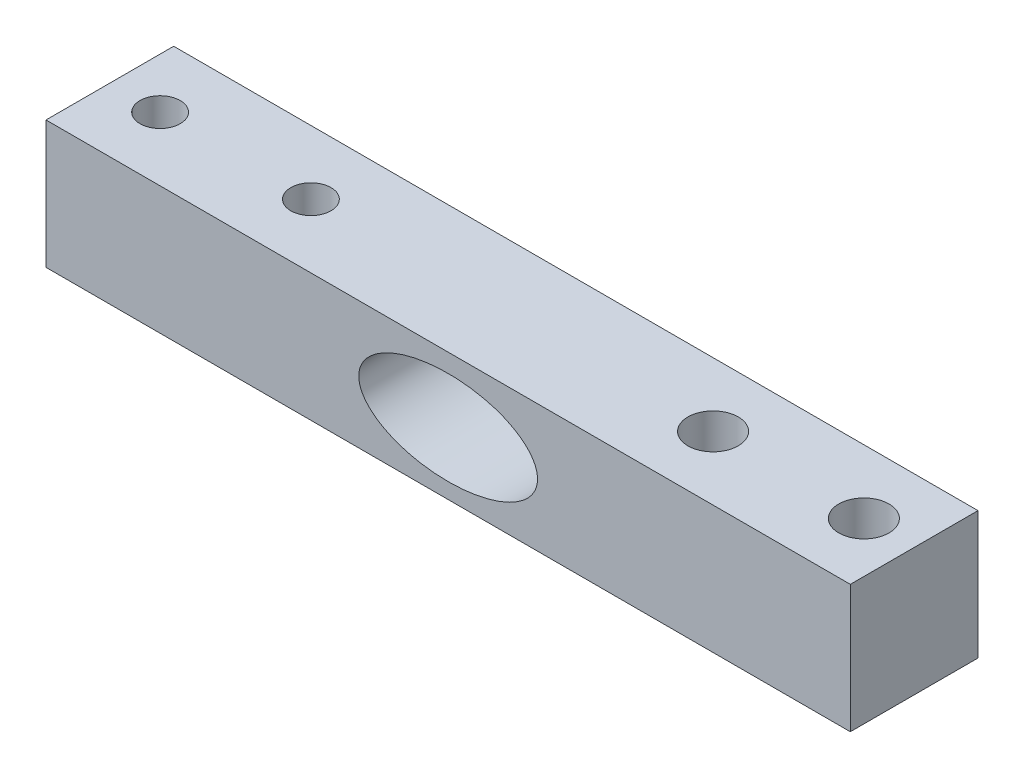
SolidWorks part; units mm, degrees
ref_plane "Front Plane" through (0, 0, 0) normal (0, 0, 1) x (1, 0, 0)
ref_plane "Top Plane" through (0, 0, 0) normal (0, 1, 0) x (1, 0, 0)
ref_plane "Right Plane" through (0, 0, 0) normal (1, 0, 0) x (0, 0, -1)
sketch "Sketch2" plane through (0, 0, 0) normal (0, 1, 0) x (1, 0, 0)
  line L1 (40, -6.35) -> (-40, -6.35)
  line L2 (40, -6.35) -> (40, 6.35)
  line L3 (40, 6.35) -> (-40, 6.35)
  line L4 (-40, -6.35) -> (-40, 6.35)
  line L5 (40, -6.35) -> (-40, 6.35) construction
  line L6 (40, 6.35) -> (-40, -6.35) construction
  point P0 (0, 0)
  dimension "D1" = 80
  dimension "D2" = 12.7
extrude "Boss-Extrude1" add sketch "Sketch2" along normal blind 12.7
sketch "Sketch3" plane through (0, 12.7, 0) normal (0, 1, 0) x (1, 0, 0)
  line L0 (-6.985, 0) -> (6.985, 0) construction
  line L1 (-40, 6.35) -> (-40, -6.35) construction
  line L2 (40, -6.35) -> (40, 6.35) construction
  circle A0 centre (-35, 0) radius 2
  circle A1 centre (-20, 0) radius 2
  circle A2 centre (35, 0) radius 2.5
  circle A3 centre (20, 0) radius 2.5
  dimension "D1" = 4
  dimension "D2" = 4
  dimension "D3" = 5
  dimension "D4" = 5
  dimension "D5" = 15
  dimension "D6" = 15
  dimension "D7" = 5
  dimension "D8" = 5
extrude "Cut-Extrude1" cut sketch "Sketch3" against normal through all
sketch "Sketch4" plane through (0, 0, 6.35) normal (0, 0, 1) x (1, 0, 0)
  line L0 (0, -6.985) -> (0, 6.985) construction
  ellipse E0 centre (0, 6.2078) end of major axis (8.89, 6.2078) minor radius 4.6609
  dimension "D1" = 8.89
  dimension "D2" = 4.6609
extrude "Cut-Extrude3" cut sketch "Sketch4" against normal through all contours E0
